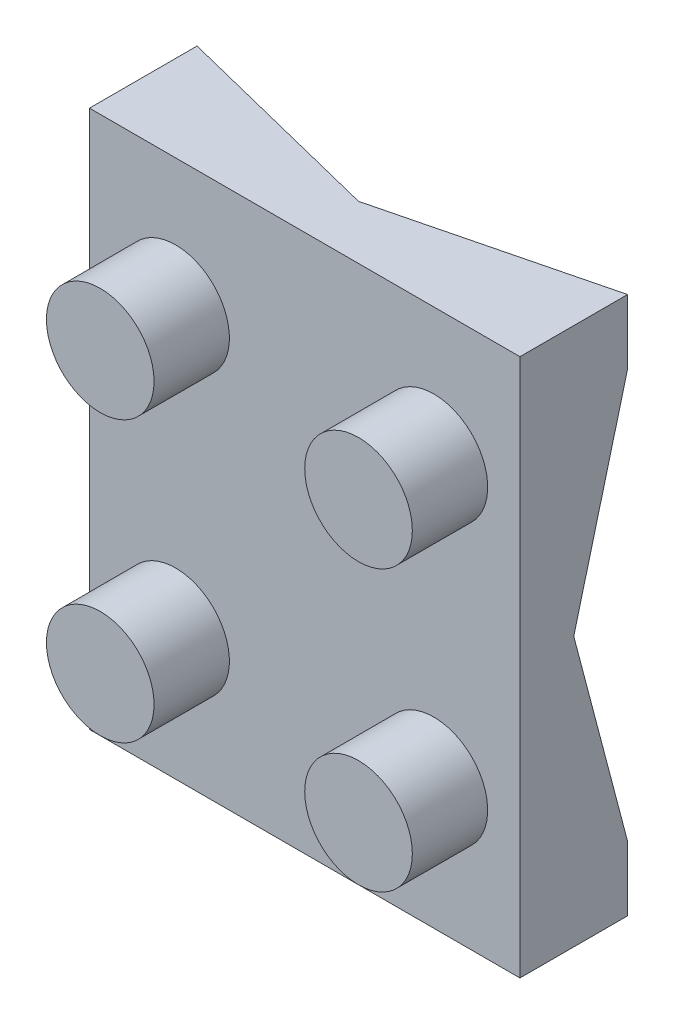
SolidWorks part; units mm, degrees
material "Silicon"
ref_plane "Front Plane" through (0, 0, 0) normal (0, 0, 1) x (1, 0, 0)
ref_plane "Top Plane" through (0, 0, 0) normal (0, 1, 0) x (1, 0, 0)
ref_plane "Right Plane" through (0, 0, 0) normal (1, 0, 0) x (0, 0, -1)
sketch "Sketch1" plane through (0, 0, 0) normal (0, 0, 1) x (1, 0, 0)
  line L1 (0, 0) -> (20, 0)
  line L2 (0, 0) -> (0, 25)
  line L3 (0, 25) -> (20, 25)
  line L4 (20, 0) -> (20, 25)
  dimension "D1" = 20
  dimension "D2" = 25
extrude "Boss-Extrude1" add sketch "Sketch1" along normal blind 5
sketch "Sketch2" plane through (0, 0, 5) normal (0, 0, 1) x (1, 0, 0)
  line L0 (4, 25) -> (4, 19) construction
  line L1 (20, 25) -> (0, 25) construction
  line L2 (4, 19) -> (0, 19) construction
  line L3 (0, 25) -> (0, 0) construction
  line L4 (0, 6) -> (4, 6) construction
  line L5 (4, 6) -> (4, 0) construction
  line L6 (0, 0) -> (20, 0) construction
  line L7 (16, 25) -> (16, 19) construction
  line L8 (16, 19) -> (20, 19) construction
  line L9 (20, 0) -> (20, 25) construction
  line L10 (20, 6) -> (16, 6) construction
  line L11 (16, 6) -> (16, 0) construction
  circle A0 centre (4, 19) radius 2.5
  circle A1 centre (16, 19) radius 2.5
  circle A2 centre (16, 6) radius 2.5
  circle A3 centre (4, 6) radius 2.5
  dimension "D9" = 5
  dimension "D10" = 5
  dimension "D11" = 5
  dimension "D12" = 5
  dimension "D1" = 4
  dimension "D2" = 4
  dimension "D3" = 4
  dimension "D4" = 4
  dimension "D5" = 6
  dimension "D6" = 6
  dimension "D7" = 6
  dimension "D8" = 6
extrude "Boss-Extrude2" add sketch "Sketch2" along normal blind 3.5
sketch "Sketch3" plane through (20, 0, 0) normal (1, 0, 0) x (0, 0, -1)
  line L0 (-5, 12.5) -> (0, 12.5) construction
  line L1 (-5, 0) -> (-5, 25) construction
  line L2 (0, 0) -> (0, 25) construction
  line L3 (0, 25) -> (0, 22)
  line L4 (0, 22) -> (-2.5, 12.5)
  line L5 (-2.5, 12.5) -> (0, 3)
  line L6 (0, 3) -> (0, 0)
  line L7 (0, 22) -> (0, 3)
  line M5 (0, 0) -> (0, 25)
  dimension "D1" = 3
  dimension "D2" = 3
  dimension "D3" = 2.5
extrude "Cut-Extrude1" cut sketch "Sketch3" against normal blind 23.5 contours L4 L0 L7 | L0 L5 M5
sketch "Sketch4" plane through (0, 0, 0) normal (0, -1, 0) x (-1, 0, 0)
  line L0 (-10, -5) -> (-10, 0) construction
  line L1 (0, -5) -> (-20, -5) construction
  line L2 (0, 0) -> (-20, 0) construction
  line L3 (0, 0) -> (-10, -2.5)
  line L4 (-10, -2.5) -> (-20, 0)
  line L5 (0, 0) -> (-20, 0)
  dimension "D1" = 2.5
extrude "Cut-Extrude2" cut sketch "Sketch4" against normal blind 33.5
